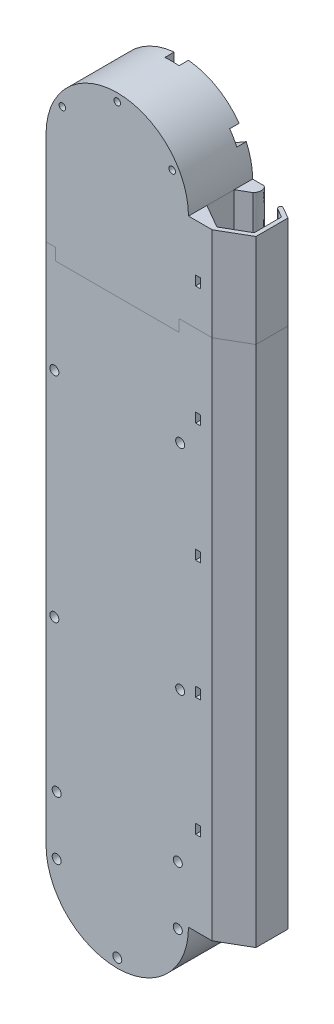
SolidWorks part; units mm, degrees
ref_plane "Front Plane" through (0, 0, 0) normal (0, 0, 1) x (1, 0, 0)
ref_plane "Top Plane" through (0, 0, 0) normal (0, 1, 0) x (1, 0, 0)
ref_plane "Right Plane" through (0, 0, 0) normal (1, 0, 0) x (0, 0, -1)
sketch "Sketch1" plane through (0, 0, 0) normal (0, 0, 1) x (1, 0, 0)
  line L0 (0, -129.7) -> (0, 129.7) construction
  line L1 (-30, -129.7) -> (-30, 129.7)
  line L2 (30, -129.7) -> (30, 129.7)
  line L3 (-22, -129.7) -> (-22, 129.7)
  line L4 (22, -129.7) -> (22, 129.7)
  arc A0 (-30, -129.7) -> (30, -129.7) centre (0, -129.7) ccw
  arc A1 (30, 129.7) -> (-30, 129.7) centre (0, 129.7) ccw
  arc A2 (22, 129.7) -> (-22, 129.7) centre (0, 129.7) ccw
  arc A3 (-22, -129.7) -> (22, -129.7) centre (0, -129.7) ccw
  point P3 (0, 0)
  point P14 (0, -159.7)
  point P15 (0, 0)
  point P16 (0, 0)
  point P17 (0, 159.7)
  point P18 (0, 0)
  point P19 (-122.8291, 30)
  point P20 (0, 0)
  point P21 (0, 0)
  point P22 (0, 0)
  dimension "D1" = 30
  dimension "D3" = 319.4
  dimension "D2" = 8
extrude "Boss-Extrude1" add sketch "Sketch1" along normal blind 25
sketch "Sketch5" plane through (0, 0, 0) normal (0, 0, 1) x (1, 0, 0)
  line L7 (30, -196.9762) -> (30, 129.7)
  line L8 (-30, 129.7) -> (-30, -196.9762)
  line L11 (-18.5, -115.3) -> (-18.5, -125.3)
  line L12 (18.5, -125.3) -> (18.5, -115.3)
  arc A8 (-30, -196.9762) -> (30, -196.9762) centre (0, -220.3) ccw
  arc A9 (30, 129.7) -> (-30, 129.7) centre (0, 129.7) ccw
  circle A10 centre (25.5, -108.05) radius 1.9
  circle A12 centre (25.5, -132.55) radius 1.9
  circle A14 centre (-25.5, -108.05) radius 1.9
  arc A18 (-18.5, -125.3) -> (18.5, -125.3) centre (0, -125.3) ccw
  arc A19 (18.5, -115.3) -> (-18.5, -115.3) centre (0, -115.3) ccw
  circle A20 centre (20.4, -220.3) radius 1.9
  circle A22 centre (14.425, -234.725) radius 1.9
  circle A24 centre (0, -240.7) radius 1.9
  circle A26 centre (-14.425, -234.725) radius 1.9
  circle A28 centre (-20.4, -220.3) radius 1.9
  circle A30 centre (-14.425, -205.875) radius 1.9
  circle A32 centre (0, -199.9) radius 1.9
  circle A34 centre (14.425, -205.875) radius 1.9
  circle A36 centre (0, 156.4) radius 1.4
  circle A38 centre (-23.1229, 143.05) radius 1.4
  circle A40 centre (-23.1229, 116.35) radius 1.4
  circle A42 centre (0, 103) radius 1.4
  circle A44 centre (23.1229, 116.35) radius 1.4
  circle A46 centre (23.1229, 143.05) radius 1.4
  circle A48 centre (0, -220.3) radius 15
  circle A50 centre (0, 129.7) radius 23.5
  circle A52 centre (9.2841, 59.323) radius 0.9
  circle A54 centre (-25.5, -132.55) radius 1.9
  circle A56 centre (14.12, 67.5) radius 0.9
  circle A58 centre (0, -155.8) radius 1.9
  circle A60 centre (-26.5, -89.8) radius 1.9
  circle A62 centre (0, 43.2) radius 1.9
  circle A64 centre (0, 3.2) radius 1.9
  circle A66 centre (0, -36.8) radius 1.9
  circle A68 centre (0, -76.8) radius 1.9
  circle A70 centre (26.5, -89.8) radius 1.9
  circle A72 centre (26.5, -44.8) radius 1.9
  circle A74 centre (26.5, 0.2) radius 1.9
  circle A76 centre (26.5, 45.2) radius 1.9
  circle A78 centre (26.5, 90.2) radius 1.9
  circle A80 centre (-26.5, 90.2) radius 1.9
  circle A82 centre (-26.5, 45.2) radius 1.9
  circle A84 centre (-26.5, 0.2) radius 1.9
  circle A86 centre (-26.5, -44.8) radius 1.9
sketch "Sketch9" plane through (0, 0, 0) normal (0, 0, 1) x (1, 0, 0)
  line L0 (-21.3902, -156.8041) -> (-12.1976, -143.1635)
  line L1 (-12.1976, -143.1635) -> (11.5252, -143.1635)
  line L2 (11.5252, -143.1635) -> (24.2762, -155.9145)
  line L3 (24.2762, -155.9145) -> (43.1061, -137.0846)
  line L4 (43.1061, -137.0846) -> (43.1061, -85.3392)
  line L5 (43.1061, -85.3392) -> (-47.337, -85.3392)
  line L6 (-47.337, -85.3392) -> (-47.337, -133.3779)
  line L7 (-47.337, -133.3779) -> (-21.3902, -156.8041)
extrude "Cut-Extrude2" cut sketch "Sketch9" along normal blind 6
extrude "Cut-Extrude4" cut sketch "Sketch5" along normal through all contours A58 | A72 | A76 | A82 | A86 | A36 | A38 | A40 | A44 | A10 | A12 | A54 | A14 | A46
sketch "Sketch10" plane through (0, 0, 0) normal (0, 0, -1) x (-1, 0, 0)
  line L0 (-3.6, -157.8785) -> (-3.6, -162.7172)
  line L1 (3.6, -157.8785) -> (3.6, -153.7215)
  line L2 (3.6, -153.7215) -> (0, -151.6431)
  line L3 (0, -151.6431) -> (-3.6, -153.7215)
  line L4 (-3.6, -153.7215) -> (-3.6, -157.8785)
  line L5 (-3.6, -157.8785) -> (0, -159.9569) construction
  line L6 (0, -159.9569) -> (3.6, -157.8785) construction
  line L7 (-3.6, -162.7172) -> (3.6, -162.7172)
  line L8 (3.6, -162.7172) -> (3.6, -157.8785)
  line L9 (24.4215, -48.4) -> (16.2025, -53.1453)
  line L10 (-30.6569, -44.8) -> (-28.5785, -48.4)
  line L11 (-28.5785, -48.4) -> (-24.4215, -48.4)
  line L12 (-24.4215, -48.4) -> (-22.3431, -44.8) construction
  line L13 (-22.3431, -44.8) -> (-24.4215, -41.2) construction
  line L14 (-24.4215, -41.2) -> (-28.5785, -41.2)
  line L15 (-28.5785, -41.2) -> (-30.6569, -44.8)
  line L16 (30.6569, -44.8) -> (28.5785, -41.2)
  line L17 (28.5785, -41.2) -> (24.4215, -41.2)
  line L18 (24.4215, -41.2) -> (22.3431, -44.8) construction
  line L19 (22.3431, -44.8) -> (24.4215, -48.4) construction
  line L20 (24.4215, -48.4) -> (28.5785, -48.4)
  line L21 (28.5785, -48.4) -> (30.6569, -44.8)
  line L22 (-30.6569, 45.2) -> (-28.5785, 41.6)
  line L23 (-28.5785, 41.6) -> (-24.4215, 41.6)
  line L24 (-24.4215, 41.6) -> (-22.3431, 45.2) construction
  line L25 (-22.3431, 45.2) -> (-24.4215, 48.8) construction
  line L26 (-24.4215, 48.8) -> (-28.5785, 48.8)
  line L27 (-28.5785, 48.8) -> (-30.6569, 45.2)
  line L28 (30.6569, 45.2) -> (28.5785, 48.8)
  line L29 (28.5785, 48.8) -> (24.4215, 48.8)
  line L30 (24.4215, 48.8) -> (22.3431, 45.2) construction
  line L31 (22.3431, 45.2) -> (24.4215, 41.6) construction
  line L32 (24.4215, 41.6) -> (28.5785, 41.6)
  line L33 (28.5785, 41.6) -> (30.6569, 45.2)
  line L34 (16.2025, -53.1453) -> (16.2025, -37.2496)
  line L35 (16.2025, -37.2496) -> (24.4215, -41.2)
  line L36 (24.4215, 48.8) -> (16.2025, 49.3071)
  line L37 (16.2025, 49.3071) -> (16.6636, 39.5209)
  line L38 (16.6636, 39.5209) -> (24.4215, 41.6)
  line L39 (-24.4215, 48.8) -> (-19.0651, 53.1026)
  line L40 (-19.0651, 53.1026) -> (-19.0651, 37.9941)
  line L41 (-19.0651, 37.9941) -> (-24.4215, 41.6)
  line L42 (-24.4215, -48.4) -> (-20.4006, -51.4249)
  line L43 (-20.4006, -51.4249) -> (-19.5264, -39.2739)
  line L44 (-19.5264, -39.2739) -> (-24.4215, -41.2)
  circle A0 centre (0, -155.8) radius 3.6 construction
  circle A1 centre (-26.5, -44.8) radius 3.6 construction
  circle A2 centre (26.5, -44.8) radius 3.6 construction
  circle A3 centre (-26.5, 45.2) radius 3.6 construction
  circle A4 centre (26.5, 45.2) radius 3.6 construction
  dimension "D1" = 7.2
  dimension "D2" = 7.2
extrude "Cut-Extrude3" cut sketch "Sketch10" against normal blind 4 from offset 2 offset against normal yes
sketch "Sketch12" plane through (0, 0, 25) normal (0, 0, 1) x (1, 0, 0)
  line L7 (22, 117.1861) -> (22, 129.7)
  line L9 (22, -129.7) -> (22, 115.5139)
  line L10 (-22, 115.5139) -> (-22, -129.7)
  line L11 (-22, 129.7) -> (-22, 117.1861)
  line L16 (22, 117.1861) -> (22, 129.7)
  line L17 (22, -129.7) -> (22, 115.5139)
  line L18 (-22, 115.5139) -> (-22, -129.7)
  line L19 (-22, 129.7) -> (-22, 117.1861)
  circle A1 centre (26.5, -44.8) radius 1.9
  circle A7 centre (26.5, -44.8) radius 1.9
  circle A17 centre (26.5, 45.2) radius 1.9
  arc A19 (22, 115.5139) -> (22, 117.1861) centre (23.1229, 116.35) ccw
  arc A21 (-22, -129.7) -> (22, -129.7) centre (0, -129.7) ccw
  arc A23 (-22, 117.1861) -> (-22, 115.5139) centre (-23.1229, 116.35) ccw
  arc A25 (22, 129.7) -> (-22, 129.7) centre (0, 129.7) ccw
  arc A27 (22, 115.5139) -> (22, 117.1861) centre (23.1229, 116.35) ccw
  arc A29 (-22, -129.7) -> (22, -129.7) centre (0, -129.7) ccw
  arc A30 (-22, 117.1861) -> (-22, 115.5139) centre (-23.1229, 116.35) ccw
  arc A31 (22, 129.7) -> (-22, 129.7) centre (0, 129.7) ccw
  circle A32 centre (26.5, 45.2) radius 1.9
  circle A33 centre (-26.5, 45.2) radius 1.9
  circle A34 centre (-26.5, 45.2) radius 1.9
  circle A35 centre (-26.5, -44.8) radius 1.9
  circle A36 centre (-26.5, -44.8) radius 1.9
  circle A37 centre (0, 156.4) radius 1.4
  circle A38 centre (0, 156.4) radius 1.4
  circle A39 centre (-23.1229, 143.05) radius 1.4
  circle A40 centre (-23.1229, 143.05) radius 1.4
  circle A41 centre (23.1229, 143.05) radius 1.4
  circle A42 centre (23.1229, 143.05) radius 1.4
  circle A43 centre (0, -155.8) radius 1.9
  circle A44 centre (0, -155.8) radius 1.9
  circle M32 centre (0, -155.8) radius 1.9
  circle M33 centre (23.1229, 143.05) radius 1.4
  circle M34 centre (-23.1229, 143.05) radius 1.4
  circle M35 centre (0, 156.4) radius 1.4
  circle M36 centre (-26.5, -44.8) radius 1.9
  circle M37 centre (-26.5, 45.2) radius 1.9
  circle M38 centre (26.5, 45.2) radius 1.9
  circle M39 centre (26.5, -44.8) radius 1.9
  arc M40 (-30, -129.7) -> (30, -129.7) centre (0, -129.7) ccw
  line M41 (30, -129.7) -> (30, 129.7)
  arc M42 (30, 129.7) -> (-30, 129.7) centre (0, 129.7) ccw
  line M43 (-30, 129.7) -> (-30, -129.7)
  line M44 (22, 129.7) -> (22, 117.1861)
  arc M45 (22, 117.1861) -> (22, 115.5139) centre (23.1229, 116.35) cw
  line M46 (22, 115.5139) -> (22, -129.7)
  arc M47 (22, -129.7) -> (-22, -129.7) centre (0, -129.7) cw
  line M48 (-22, -129.7) -> (-22, 115.5139)
  arc M49 (-22, 115.5139) -> (-22, 117.1861) centre (-23.1229, 116.35) cw
  line M50 (-22, 117.1861) -> (-22, 129.7)
  arc M51 (-22, 129.7) -> (22, 129.7) centre (0, 129.7) cw
  dimension "D1" = 0
  dimension "D2" = 0
  dimension "D3" = 0
  dimension "D4" = 0
  dimension "D5" = 0
  dimension "D6" = 0
  dimension "D7" = 0
  dimension "D8" = 0
  dimension "D9" = 0
extrude "Boss-Extrude2" add sketch "Sketch12" along normal blind 2 contours M43 M40 M41 M42 M33 M35 M37 M39 M51 M44 M45 M46 M47 M48 M49 M50 M38 M36 M34 M32 | M44 M51 M50 M49 M48 M47 M46 M45
sketch "Sketch13" plane through (0, 0, 0) normal (0, 1, 0) x (1, 0, 0)
  line L0 (30, -27) -> (30, 0) construction
  line L1 (51.6506, -6.75) -> (39.9593, 0)
  line L2 (39.9593, 0) -> (28.2679, -6.75)
  line L3 (28.2679, -6.75) -> (28.2679, -20.25)
  line L4 (28.2679, -20.25) -> (39.9593, -27)
  line L5 (39.9593, -27) -> (51.6506, -20.25)
  line L6 (51.6506, -20.25) -> (51.6506, -6.75)
  line L7 (-30, -27) -> (30, -27) construction
  line L8 (39.9593, -27) -> (28.2679, -27)
  line L9 (39.9593, 0) -> (28.2679, 0)
  line L10 (28.2679, -20.25) -> (28.2679, -27)
  line L11 (39.9593, -25) -> (49.9186, -19.25)
  line L12 (49.9186, -19.25) -> (49.9186, -7.75)
  line L13 (49.9186, -7.75) -> (39.9593, -2)
  line L14 (39.9593, -2) -> (30, -7.75)
  line L15 (30, -7.75) -> (30, -19.25)
  line L16 (30, -19.25) -> (39.9593, -25)
  line L17 (28.2679, -6.75) -> (28.2679, 0)
  line L18 (30, 0) -> (30, -27)
  circle A0 centre (39.9593, -13.5) radius 11.6913 construction
  circle A1 centre (39.9593, -13.5) radius 9.9593 construction
  point P9 (30, -13.5)
  dimension "D1" = 2
extrude "Boss-Extrude3" add sketch "Sketch13" against normal up to vertex (129.7 mm away) from vertex at 129.7 contours L9 L18 L2 | L2 L18 L14 L13 L12 L11 L16 L4 L5 L6 L1 | L4 L18 L8
sketch "Sketch14" plane through (0, 129.7, 0) normal (0, 1, 0) x (1, 0, 0)
  line L0 (34.7536, 0) -> (41.39, 4.8138)
  line L1 (41.39, 4.8138) -> (46.7055, -3.8949)
  line L3 (34.1247, -5.3686) -> (46.2195, -5.6143)
  line L4 (51.6506, -6.75) -> (39.9593, 0) construction
  line L5 (49.9186, -7.75) -> (39.9593, -2) construction
  line L6 (39.9593, 0) -> (30, 0) construction
  line L7 (39.9593, -2) -> (30, -7.75) construction
  line L8 (46.2195, -5.6143) -> (45.1365, -4.9891) construction
  line L9 (45.1365, -4.9891) -> (45.7519, -3.4803) construction
  line L10 (45.7519, -3.4803) -> (46.7055, -3.8949) construction
  line L11 (34.1247, -5.3686) -> (36.3212, -4.6957) construction
  line L12 (36.3212, -4.6957) -> (36.7459, -0.7858) construction
  line L13 (36.7459, -0.7858) -> (34.7536, 0) construction
  spline S0 degree 3 poles (46.2195, -5.6143) (45.1365, -4.9891) (45.7519, -3.4803) (46.7055, -3.8949) knots 0 0 0 0 1 1 1 1
  spline S1 degree 3 poles (34.1247, -5.3686) (36.3212, -4.6957) (36.7459, -0.7858) (34.7536, 0) knots 0 0 0 0 1 1 1 1
  point P11 (36.7459, -0.7858)
  point P14 (36.3212, -4.6957)
  point P15 (45.1365, -4.9891)
  point P18 (45.7519, -3.4803)
extrude "Cut-Extrude5" cut sketch "Sketch14" against normal through all
sketch "Sketch15" plane through (0, 0, 27) normal (0, 0, 1) x (1, 0, 0)
  line L0 (34.9965, 59.7) -> (34.9965, 55.7)
  line L5 (32.9965, 109.7) -> (34.9965, 109.7)
  line L6 (32.9965, 109.7) -> (32.9965, 105.7)
  line L11 (32.9965, 105.7) -> (34.9965, 105.7)
  line L12 (34.9965, 109.7) -> (34.9965, 105.7)
  line L17 (32.9965, 109.7) -> (34.9965, 105.7) construction
  line L18 (32.9965, 105.7) -> (34.9965, 109.7) construction
  line L23 (32.9965, 55.7) -> (34.9965, 55.7)
  line L24 (32.9965, 59.7) -> (32.9965, 55.7)
  line L29 (32.9965, 59.7) -> (34.9965, 59.7)
  line L30 (34.9965, 9.7) -> (34.9965, 5.7)
  line L31 (32.9965, 5.7) -> (34.9965, 5.7)
  line L32 (32.9965, 9.7) -> (32.9965, 5.7)
  line L33 (32.9965, 9.7) -> (34.9965, 9.7)
  line L34 (34.9965, -40.3) -> (34.9965, -44.3)
  line L35 (32.9965, -44.3) -> (34.9965, -44.3)
  line L36 (32.9965, -40.3) -> (32.9965, -44.3)
  line L37 (32.9965, -40.3) -> (34.9965, -40.3)
  line L38 (34.9965, -90.3) -> (34.9965, -94.3)
  line L39 (32.9965, -94.3) -> (34.9965, -94.3)
  line L40 (32.9965, -90.3) -> (32.9965, -94.3)
  line L41 (32.9965, -90.3) -> (34.9965, -90.3)
  line L42 (34.9965, 109.7) -> (34.9965, 59.7) construction
  line L43 (39.9593, 129.7) -> (30, 129.7) construction
  point P0 (33.9965, 107.7)
  point P5 (0, 0)
  dimension "D1" = 2
  dimension "D2" = 4
  dimension "D4" = 50
  dimension "D5" = 20
  dimension "D3" = 5
extrude "Cut-Extrude6" cut sketch "Sketch15" against normal up to next
sketch "Sketch17" plane through (0, 0, 27) normal (0, 0, 1) x (1, 0, 0)
  line L0 (0, -159.7) -> (0, 85.3) construction
  line L1 (-56.5815, 90.3) -> (-26, 90.3)
  line L2 (-0.3549, 85.3) -> (-26, 85.3)
  line L3 (-26, 85.3) -> (-26, 90.3)
  line L4 (-56.5815, 90.3) -> (-47.8303, 186.7894)
  line L5 (-47.8303, 186.7894) -> (80.7353, 186.7894)
  line L6 (80.7353, 186.7894) -> (80.7353, 90.3)
  line L7 (26, 90.3) -> (26, 85.3)
  line L8 (26, 85.3) -> (-0.3549, 85.3)
  line L9 (-22, 115.5139) -> (-22, -129.7) construction
  line L10 (22, -129.7) -> (22, 115.5139) construction
  line L11 (0, 85.3) -> (0, 90.3) construction
  line L12 (0, 90.3) -> (26, 90.3) construction
  line L13 (26, 90.3) -> (80.7353, 90.3)
  line L14 (-26, 90.3) -> (0, 90.3) construction
  arc A0 (-30, -129.7) -> (30, -129.7) centre (0, -129.7) ccw construction
  dimension "D1" = 250
  dimension "D2" = 4
  dimension "D3" = 5
  dimension "D4" = 4
sketch "Sketch19" plane through (0, 0, 0) normal (0, 0, -1) x (-1, 0, 0)
  line L8 (18.2316, 136.7619) -> (31.0142, 144.1419)
  line L9 (-3, 149.02) -> (3, 149.02)
  line L10 (-3, 149.02) -> (-3, 163.78)
  line L11 (-3, 163.78) -> (3, 163.78)
  line L12 (3, 149.02) -> (3, 163.78)
  line L13 (-3, 149.02) -> (3, 163.78) construction
  line L14 (-3, 163.78) -> (3, 149.02) construction
  line L15 (28.0142, 149.3381) -> (31.0142, 144.1419)
  line L16 (15.2316, 141.9581) -> (28.0142, 149.3381)
  line L17 (15.2316, 141.9581) -> (18.2316, 136.7619)
  line L18 (15.2316, 117.4419) -> (28.0142, 110.0619) [skipped]
  line L19 (31.0142, 115.2581) -> (28.0142, 110.0619) [skipped]
  line L20 (18.2316, 122.6381) -> (31.0142, 115.2581) [skipped]
  line L21 (18.2316, 122.6381) -> (15.2316, 117.4419) [skipped]
  line L22 (-3, 110.38) -> (-3, 95.62) [skipped]
  line L23 (3, 95.62) -> (-3, 95.62) [skipped]
  line L24 (3, 110.38) -> (3, 95.62) [skipped]
  line L25 (3, 110.38) -> (-3, 110.38) [skipped]
  line L26 (-18.2316, 122.6381) -> (-31.0142, 115.2581) [skipped]
  line L27 (-28.0142, 110.0619) -> (-31.0142, 115.2581) [skipped]
  line L28 (-15.2316, 117.4419) -> (-28.0142, 110.0619) [skipped]
  line L29 (-15.2316, 117.4419) -> (-18.2316, 122.6381) [skipped]
  line L30 (-15.2316, 141.9581) -> (-28.0142, 149.3381)
  line L31 (-31.0142, 144.1419) -> (-28.0142, 149.3381)
  line L32 (-18.2316, 136.7619) -> (-31.0142, 144.1419)
  line L33 (-18.2316, 136.7619) -> (-15.2316, 141.9581)
  arc A0 (22, 129.7) -> (-22, 129.7) centre (0, 129.7) ccw construction
  circle A1 centre (-23.1229, 116.35) radius 3
  circle A2 centre (23.1229, 116.35) radius 3
  point P0 (0, 156.4)
  point P5 (0, 129.7)
  point P33 (0, 129.7)
  dimension "D3" = 6
  dimension "D2" = 6
  dimension "D1" = 6
extrude "Cut-Extrude9" cut sketch "Sketch19" against normal blind 4
sketch "Sketch20" plane through (-30, 0, 0) normal (-1, 0, 0) x (0, 0, 1)
  line L0 (27, 129.7) -> (27, -129.7) construction
  line L1 (0, 129.7) -> (0, -85.3392) construction
  circle A0 centre (20.5, 87.8) radius 1.5
  circle A1 centre (4.5, 87.8) radius 1.5
  point P4 (22, 87.8)
  point P5 (20.5, 89.3)
  point P10 (3, 87.8)
  dimension "D1" = 3
  dimension "D2" = 1
  dimension "D3" = 5
  dimension "D4" = 3
extrude "Cut-Extrude10" cut sketch "Sketch20" against normal up to surface (60 mm away) up to face at (30, 0, 13.5)
split "Split2" trim tools "Sketch17" bodies to split 116 resulting bodies 117 118
